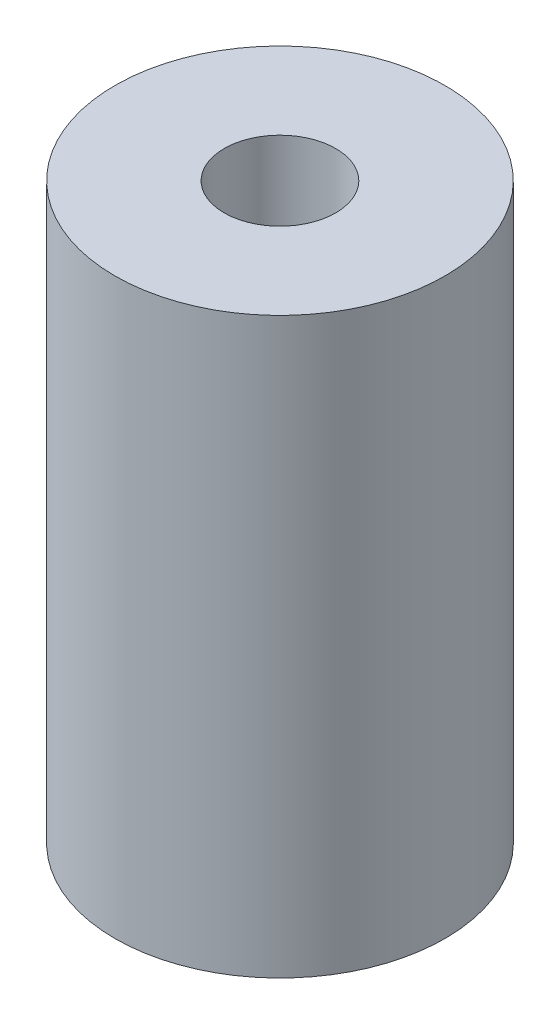
SolidWorks part; units mm, degrees
material "AP Grain"
ref_plane "Front Plane" through (0, 0, 0) normal (0, 0, 1) x (1, 0, 0)
ref_plane "Top Plane" through (0, 0, 0) normal (0, 1, 0) x (1, 0, 0)
ref_plane "Right Plane" through (0, 0, 0) normal (1, 0, 0) x (0, 0, -1)
sketch "Sketch2" plane through (0, 0, 0) normal (0, 1, 0) x (1, 0, 0)
  circle A0 centre (0, 0) radius 65.7225
  circle A1 centre (0, 0) radius 22.225
  dimension "D1" = 131.445
  dimension "D2" = 44.45
extrude "Boss-Extrude1" add sketch "Sketch2" along normal blind 228.6
